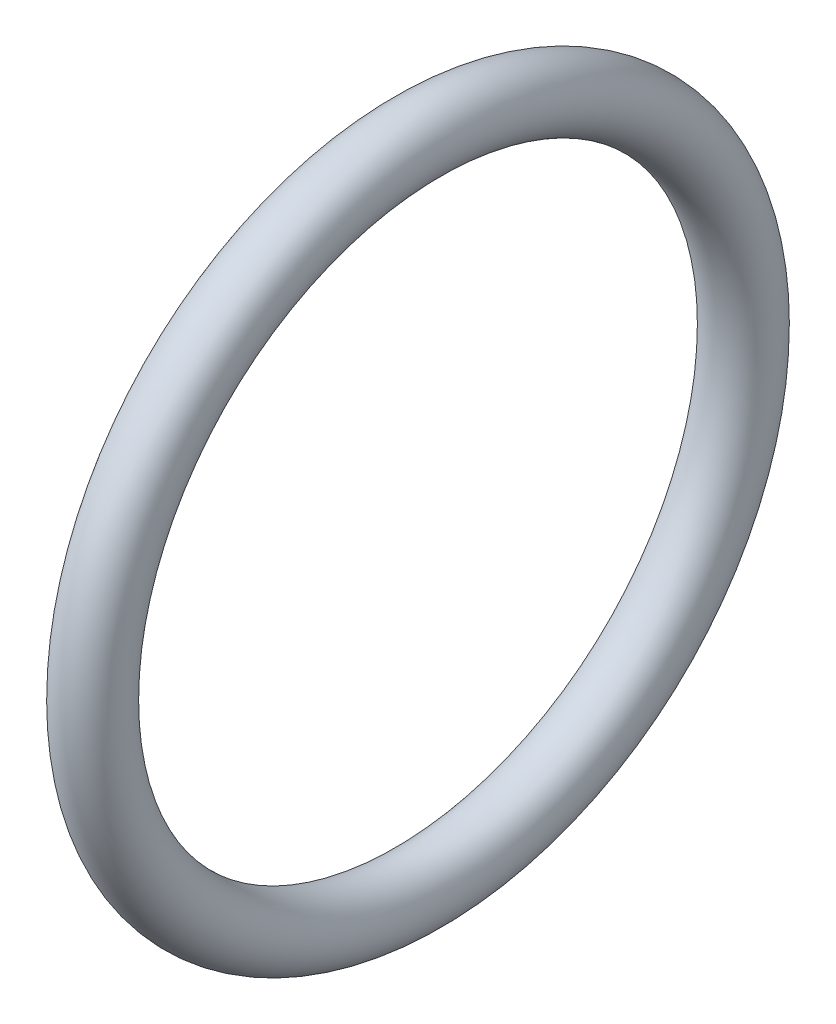
SolidWorks part; units mm, degrees
material "Caoutchouc"
ref_plane "Plan de face" through (0, 0, 0) normal (0, 0, 1) x (1, 0, 0)
ref_plane "Plan de dessus" through (0, 0, 0) normal (0, 1, 0) x (1, 0, 0)
ref_plane "Plan de droite" through (0, 0, 0) normal (1, 0, 0) x (0, 0, -1)
sketch "Esquisse1" plane through (0, 0, 0) normal (0, 0, 1) x (1, 0, 0)
  line L0 (-25.8558, 0) -> (27.968, 0) construction
  circle A0 centre (0, 16) radius 1.6
  dimension "D1" = 32
  dimension "D2" = 3.2
revolve "Révolution1" add sketch "Esquisse1" angle 360 about L0
